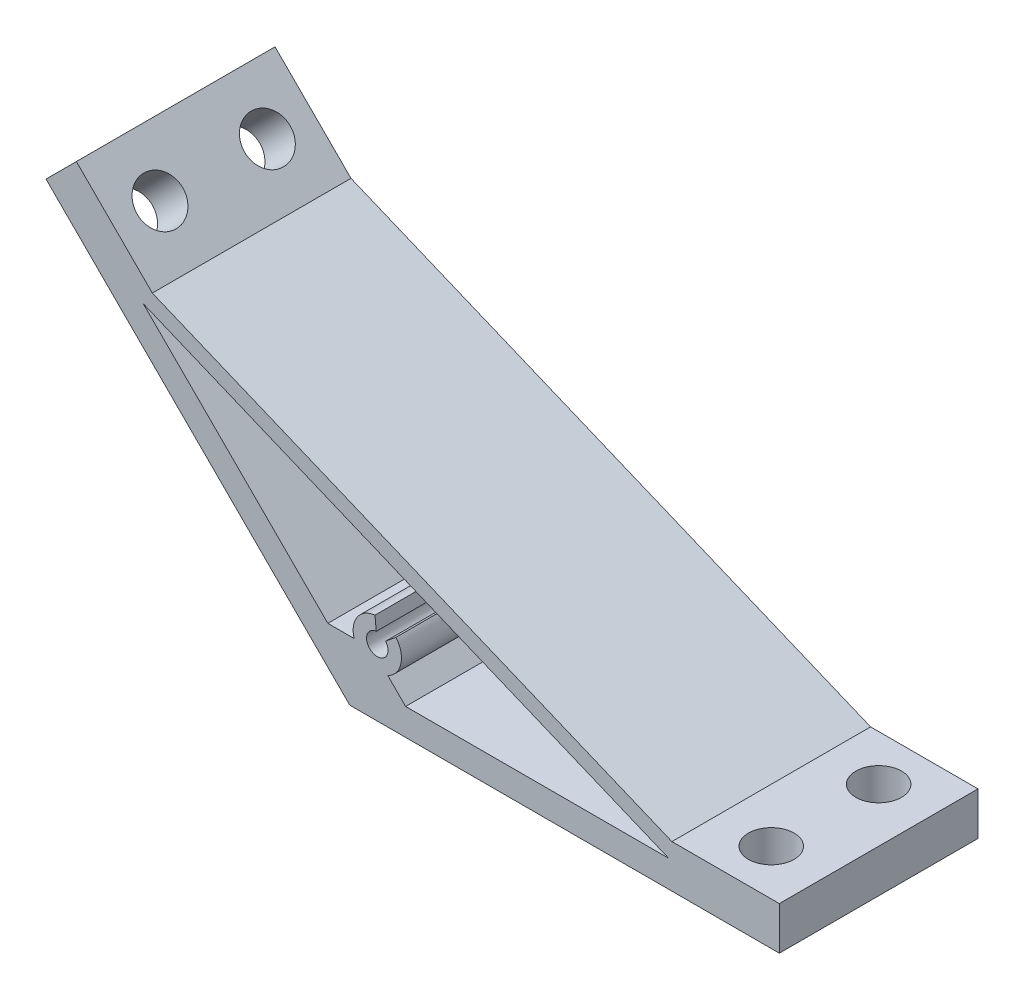
SolidWorks part; units mm, degrees
ref_plane "前视基准面" through (0, 0, 0) normal (0, 0, 1) x (1, 0, 0)
ref_plane "上视基准面" through (0, 0, 0) normal (0, 1, 0) x (1, 0, 0)
ref_plane "右视基准面" through (0, 0, 0) normal (1, 0, 0) x (0, 0, -1)
sketch "草图1" plane through (0, 0, 0) normal (0, 0, 1) x (1, 0, 0)
  line L0 (6992.6877, -1288.6549) -> (7072.6877, -1288.6549)
  line L1 (7003.0909, -1283.6549) -> (7052.0909, -1283.6549)
  line L2 (7052.6877, -1280.6549) -> (7072.6877, -1280.6549)
  line L3 (7003.0909, -1283.6549) -> (7029.4034, -1283.6549)
  line L4 (7072.6877, -1288.6549) -> (7072.6877, -1280.6549)
  line L5 (6997.6265, -1274.2736) -> (6997.3838, -1271.7854)
  line L6 (6999.3656, -1274.9939) -> (7001.2967, -1273.4062)
  line L7 (6992.6877, -1288.6549) -> (6936.1191, -1232.0864)
  line L8 (6988.6024, -1277.4986) -> (6954.2187, -1243.1149)
  line L9 (6955.9181, -1240.5717) -> (6941.776, -1226.4295)
  line L10 (6936.1191, -1232.0864) -> (6941.776, -1226.4295)
  line L11 (6955.9181, -1240.5717) -> (7052.6877, -1280.6549)
  line L12 (6954.2187, -1243.1149) -> (7052.0909, -1283.6549)
  line L13 (7052.0909, -1283.6549) -> (7009.0909, -1283.6549)
  line L14 (7003.0909, -1283.6549) -> (6999.7605, -1280.3246)
  line L15 (6988.6024, -1277.4986) -> (6993.4934, -1277.4986)
  arc A0 (6997.3838, -1271.7854) -> (6993.4934, -1277.4986) centre (6997.8207, -1276.2641) ccw
  arc A1 (6999.7605, -1280.3246) -> (7001.2967, -1273.4062) centre (6997.8207, -1276.2641) ccw
  arc A2 (6997.6265, -1274.2736) -> (6999.3656, -1274.9939) centre (6997.8207, -1276.2641) ccw
extrude "凸台-拉伸1" add sketch "草图1" along normal mid plane 37 contours L11 L9 L10 L7 L0 L4 L2 A2 L5 A0 L15 L8 L12 L1 L3 L14 A1 L6
hole_wizard "Ø8.5 (8.5) 直径孔1" positions "草图3" profile "草图2" hole size "Ø8.5" standard "GB" end condition through all
sketch "草图3" plane through (2852.0164, 2852.0164, 0) normal (-0.7071, -0.7071, 0) x (0.7071, -0.7071, 0)
  line L1 (5775.7935, 18.5) -> (5775.7935, -18.5) construction
  line L2 (5795.7935, -18.5) -> (5775.7935, -18.5) construction
  point P1 (5785.7935, -10)
  point P18 (5785.7935, 10)
  dimension "D1" = 10
  dimension "D2" = 8.5
  dimension "D3" = 2
sketch "草图2" plane through (6943.1902, -1239.1575, -10) normal (0, 0, 1) x (0.7071, -0.7071, 0)
  line L0 (0, 0) -> (0, 62.2254)
  line L1 (0, 62.2254) -> (4.25, 62.2254)
  line L2 (4.25, 62.2254) -> (4.25, 0)
  line L5 (4.25, 0) -> (0, 0)
  line L11 (0, -6.35) -> (0, 107.95) construction
  dimension "通孔孔直径" = 8.5
  dimension "通孔孔深度" = 62.2254
sketch "草图4" plane through (580.0623, 1400.3943, 0) normal (0.3827, 0.9239, 0) x (0.9239, -0.3827, 0)
  line L0 (6953.5479, -18.5) -> (6953.5479, 18.5) construction
  line L1 (6901.1766, -18.5) -> (7005.9192, -18.5) construction
  line L2 (6901.1766, 18.5) -> (7005.9192, 18.5) construction
ref_plane "基准面1" through (6424.2406, -2661.0076, 0) normal (-0.9239, 0.3827, 0) x (0, 0, 1)
mirror "镜向1" about plane through (6424.2406, -2661.0076, 0) normal (-0.9239, 0.3827, 0) of "Ø8.5 (8.5) 直径孔1"
